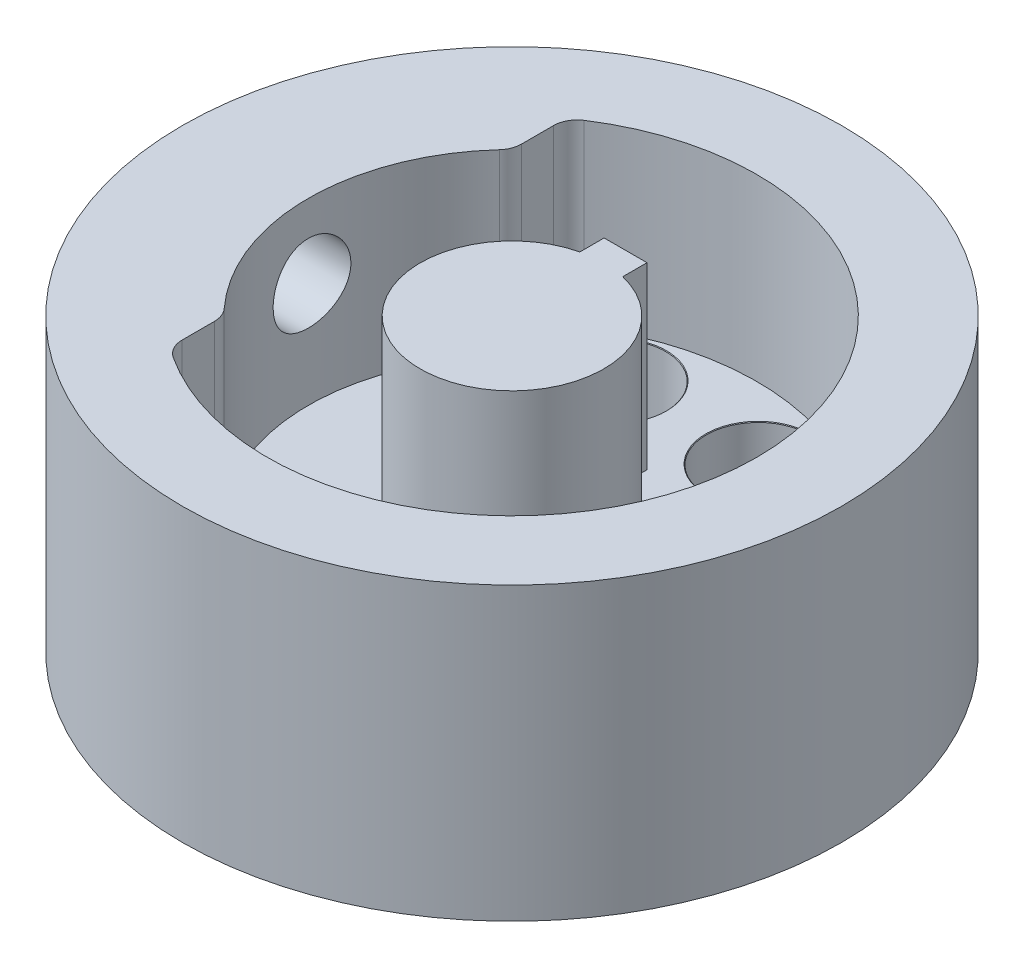
SolidWorks part; units mm, degrees
ref_plane "Front Plane" through (0, 0, 0) normal (0, 0, 1) x (1, 0, 0)
ref_plane "Top Plane" through (0, 0, 0) normal (0, 1, 0) x (1, 0, 0)
ref_plane "Right Plane" through (0, 0, 0) normal (1, 0, 0) x (0, 0, -1)
sketch "Sketch1" plane through (0, 0, 0) normal (0, 1, 0) x (1, 0, 0)
  line L0 (0, 8) -> (0, -8) construction
  line L1 (7.391, 3.0615) -> (-3.0615, 7.391) construction
  line L2 (7.391, 3.0615) -> (3.0615, -7.391) construction
  line L3 (3.0615, -7.391) -> (-7.391, -3.0615) construction
  line L4 (-3.0615, 7.391) -> (-7.391, -3.0615) construction
  line L5 (7.391, 3.0615) -> (-7.391, -3.0615) construction
  line L6 (3.0615, -7.391) -> (-3.0615, 7.391) construction
  line L7 (-8, 0) -> (8, 0) construction
  line L9 (3.0615, 7.391) -> (-7.391, 3.0615) construction
  line L10 (3.0615, 7.391) -> (7.391, -3.0615) construction
  line L11 (7.391, -3.0615) -> (-3.0615, -7.391) construction
  line L12 (-7.391, 3.0615) -> (-3.0615, -7.391) construction
  line L13 (3.0615, 7.391) -> (-3.0615, -7.391) construction
  line L14 (7.391, -3.0615) -> (-7.391, 3.0615) construction
  circle A0 centre (0, 0) radius 14
  circle A1 centre (0, 0) radius 8 construction
  dimension "D1" = 28
  dimension "D2" = 16
  dimension "D3" = 22.5
  dimension "D4" = 22.5
  dimension "D5" = 90
extrude "Boss-Extrude1" add sketch "Sketch1" against normal blind 4.75 contours A0
sketch "Sketch4" plane through (0, 0, 0) normal (0, 1, 0) x (1, 0, 0)
  line L1 (0.91, 4.822) -> (-0.91, 4.822)
  line L2 (0.91, 4.822) -> (0.91, 3.7923)
  line L3 (0.91, 3.7923) -> (-0.91, 3.7923)
  line L4 (-0.91, 4.822) -> (-0.91, 3.7923)
  line L5 (0.91, 4.822) -> (-0.91, 3.7923) construction
  line L6 (0.91, 3.7923) -> (-0.91, 4.822) construction
  circle A0 centre (0, 0) radius 3.9
  point P3 (0, 4.3072)
  dimension "D1" = 7.8
  dimension "D2" = 1.0296
  dimension "D3" = 1.82
extrude "Boss-Extrude4" add sketch "Sketch4" along normal blind 7.6142 contours L3 A0 | A0 L2 L1 L4 | L3 A0
sketch "Sketch5" plane through (0, 0, 0) normal (0, 1, 0) x (1, 0, 0)
  line L0 (0, 0) -> (-9.8995, 9.8995)
  line L1 (0, 0) -> (-9.8995, -9.8995)
  line L2 (0, 0) -> (-14, 0) construction
  line L3 (-6.1165, 12.5932) -> (-6.1165, 6.1165)
  line L4 (-6.1165, -6.1165) -> (-6.1165, -12.5932)
  circle A0 centre (0, 0) radius 8.65
  circle A1 centre (0, 0) radius 14
  circle A2 centre (0, 0) radius 14 construction
  circle A3 centre (0, 0) radius 10.4
  circle M5 centre (0, 0) radius 14
  dimension "D1" = 17.3
  dimension "D2" = 20.8
  dimension "D3" = 45
  dimension "D4" = 45
extrude "Boss-Extrude5" add sketch "Sketch5" along normal blind 7.6142 contours L2 A0 L0 A1 | A0 L2 A1 L1 | L3 L0 M5 | L4 L1 M5 | L2 A3 L0 M5 | A3 L2 A1 L1 | L3 A3 L0 | L1 A3 L4 | A3 L4 L3 M5
ref_plane "Plane1" through (-20, 0, 0) normal (1, 0, 0) x (0, 0, -1)
sketch "Sketch11" plane through (-20, 0, 0) normal (1, 0, 0) x (0, 0, -1)
  line L0 (0, 4.4892) -> (0, 7.6142) construction
  line L1 (14, 7.6142) -> (-14, 7.6142) construction
  circle A0 centre (0, 4.4892) radius 2 construction
  dimension "D2" = 4
  dimension "D1" = 3.125
hole_wizard "Tap Drill for M4x0.7 Tap2" positions "Sketch15" profile "Sketch17" hole size "M4x0.7" standard "ANSI Metric"
sketch "Sketch15" plane through (-20, 0, 0) normal (1, 0, 0) x (0, 0, -1)
  point P0 (0, 4.4892)
sketch "Sketch17" plane through (-20, 4.4892, 0) normal (0, 1, 0) x (0, 0, 1)
  line L0 (0, 0) -> (0, 14.7154)
  line L1 (0, 14.7154) -> (1.65, 13.724)
  line L2 (1.65, 13.724) -> (1.65, 0.025)
  line L3 (1.65, 0.025) -> (1.675, 0)
  line L5 (1.675, 0) -> (0, 0)
  line L6 (-1.65, 0.025) -> (-1.675, 0) construction
  line L10 (0, 14.7154) -> (-1.65, 13.724) construction
  line L11 (0, -6.35) -> (0, 107.95) construction
  dimension "Hole Dia." = 3.3
  dimension "Hole Depth" = 13.724
  dimension "Near C'Sink Dia." = 3.35
  dimension "Near C'Sink Angle" = 90
  dimension "Drill Angle" = 118
fillet "Fillet2" radius 1 4 edges at (-6.1165, 3.8071, 8.4112) (-6.1165, 3.8071, 6.1165) (-6.1165, 3.8071, -6.1165) (-6.1165, 3.8071, -8.4112)
hole_wizard "CBORE for M2 SHCS3" positions "Sketch18" profile "Sketch19" counterbore size "M2" standard "ANSI Metric"
sketch "Sketch18" plane through (0, 0, 0) normal (0, 1, 0) x (1, 0, 0)
  point P0 (-3.0615, 7.391)
  point P3 (3.0615, 7.391)
  point P6 (7.391, 3.0615)
  point P9 (7.391, -3.0615)
  point P12 (3.0615, -7.391)
  point P15 (-3.0615, -7.391)
sketch "Sketch19" plane through (-3.0615, 0, -7.391) normal (1, 0, 0) x (0, 0, 1)
  line L0 (0, 0) -> (0, 5.471)
  line L1 (0, 5.471) -> (1.2, 4.75)
  line L2 (1.2, 4.75) -> (1.2, 3.5)
  line L3 (1.2, 3.5) -> (2.2, 3.5)
  line L5 (2.2, 3.5) -> (2.2, 0.025)
  line L6 (2.2, 0.025) -> (2.225, 0)
  line L7 (2.225, 0) -> (0, 0)
  line L8 (-2.2, 0.025) -> (-2.225, 0) construction
  line L10 (0, 5.471) -> (-1.2, 4.75) construction
  line L11 (0, -6.35) -> (0, 107.95) construction
  dimension "Hole Dia." = 2.4
  dimension "Hole Depth" = 4.75
  dimension "C'Bore Dia." = 4.4
  dimension "C'Bore Depth" = 3.5
  dimension "Near C'Sink Dia." = 4.45
  dimension "Near C'Sink Angle" = 90
  dimension "Drill Angle" = 118
sketch "Sketch20" plane through (0, -4.75, 0) normal (0, -1, 0) x (1, 0, 0)
  circle A0 centre (0, 0) radius 4
  dimension "D1" = 8
extrude "Cut-Extrude2" cut sketch "Sketch20" against normal blind 2.75 contours A0
sketch "Sketch21" plane through (0, -2, 0) normal (0, -1, 0) x (-1, 0, 0)
  circle A0 centre (0, 0) radius 2
  dimension "D1" = 4
extrude "Cut-Extrude3" cut sketch "Sketch21" against normal blind 2.5
